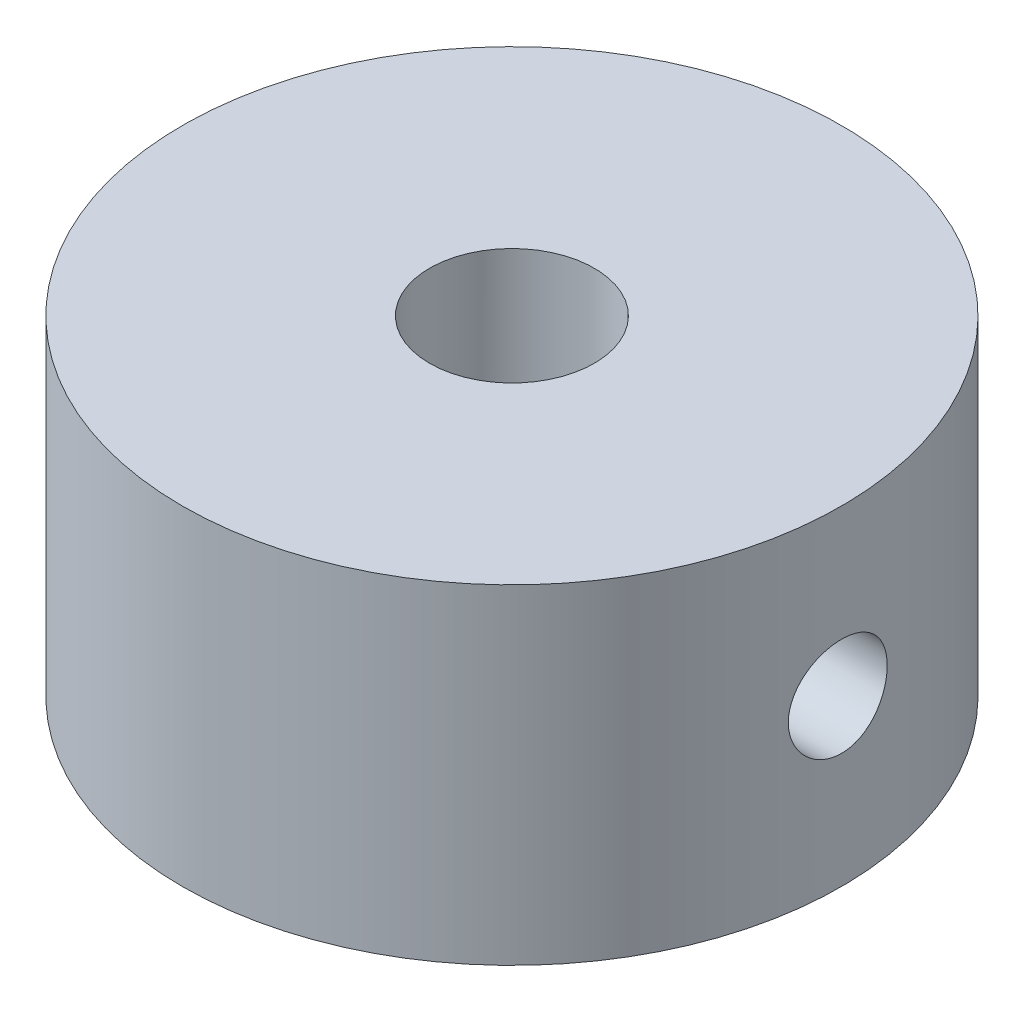
SolidWorks part; units mm, degrees
ref_plane "Front Plane" through (0, 0, 0) normal (0, 0, 1) x (1, 0, 0)
ref_plane "Top Plane" through (0, 0, 0) normal (0, 1, 0) x (1, 0, 0)
ref_plane "Right Plane" through (0, 0, 0) normal (1, 0, 0) x (0, 0, -1)
sketch "Sketch1" plane through (0, 0, 0) normal (0, 1, 0) x (1, 0, 0)
  circle A0 centre (0, 0) radius 2.5
  circle A1 centre (0, 0) radius 10
extrude "Boss-Extrude1" add sketch "Sketch1" along normal blind 10
sketch "Sketch2" plane through (0, 0, 0) normal (1, 0, 0) x (0, 0, -1)
  line L0 (0, 0) -> (0, 5) construction
  circle A0 centre (0, 5) radius 1.5
extrude "Cut-Extrude1" cut sketch "Sketch2" along normal blind 19 and the other way blind 18
